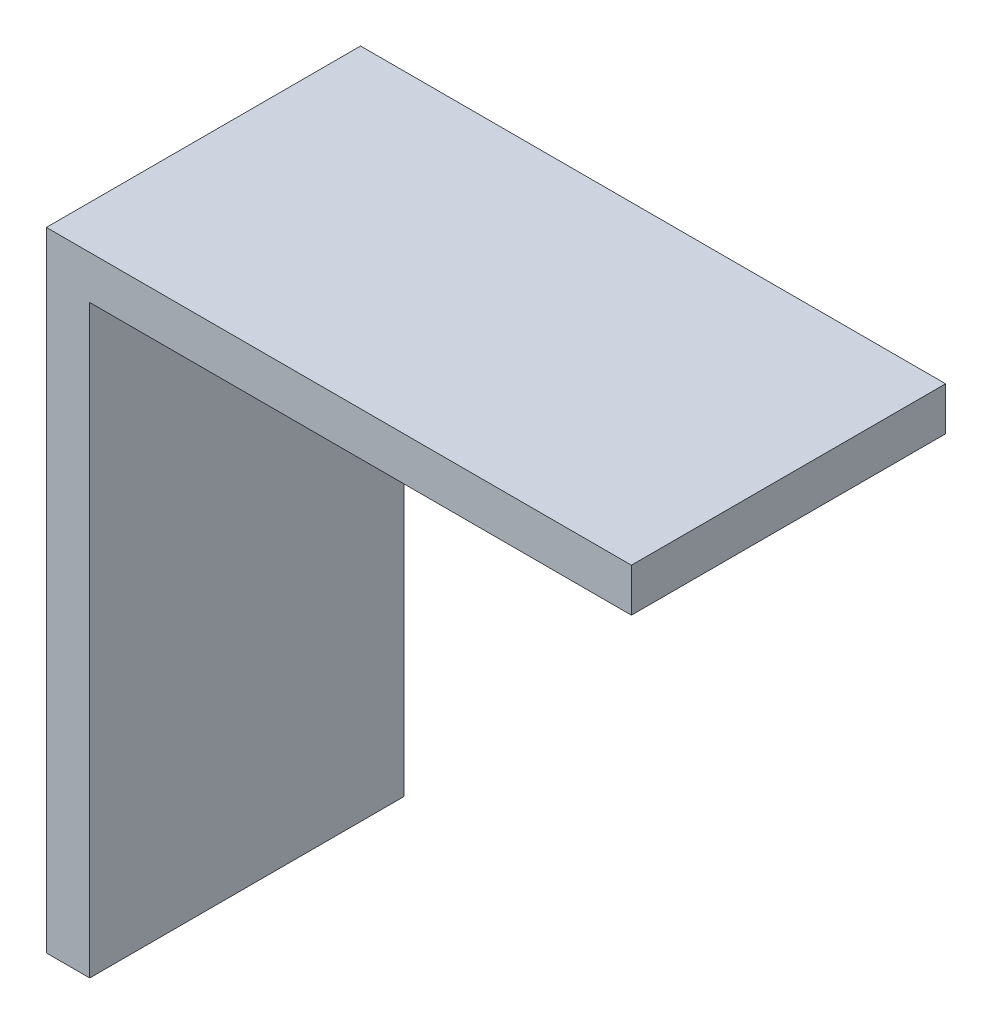
SolidWorks part; units mm, degrees
ref_plane "Спереди" through (0, 0, 0) normal (0, 0, 1) x (1, 0, 0)
ref_plane "Сверху" through (0, 0, 0) normal (0, 1, 0) x (1, 0, 0)
ref_plane "Справа" through (0, 0, 0) normal (1, 0, 0) x (0, 0, -1)
sketch "Эскиз1" plane through (0, 0, 0) normal (0, 0, 1) x (1, 0, 0)
  line L0 (0, 0) -> (0, 29)
  line L1 (0, 29) -> (27, 29)
  line L2 (27, 29) -> (27, 27)
  line L3 (27, 27) -> (2, 27)
  line L4 (2, 27) -> (2, 0)
  line L5 (2, 0) -> (0, 0)
extrude "Бобышка-Вытянуть1" add sketch "Эскиз1" along normal blind 14.5
